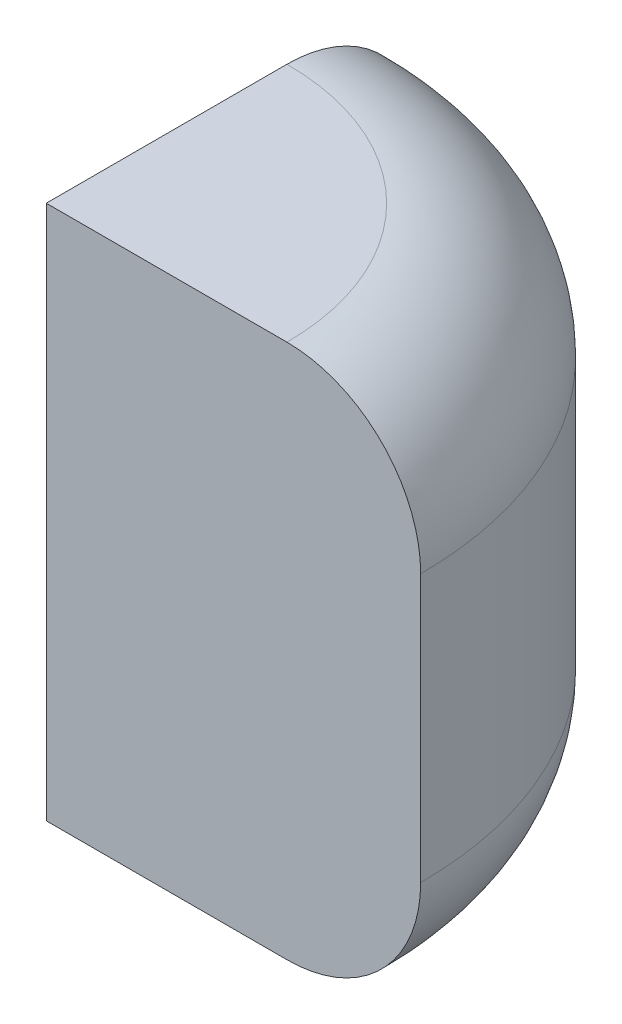
SolidWorks part; units mm, degrees
ref_plane "Front Plane" through (0, 0, 0) normal (0, 0, 1) x (1, 0, 0)
ref_plane "Top Plane" through (0, 0, 0) normal (0, 1, 0) x (1, 0, 0)
ref_plane "Right Plane" through (0, 0, 0) normal (1, 0, 0) x (0, 0, -1)
sketch "Sketch1" plane through (0, 0, 0) normal (0, 0, 1) x (1, 0, 0)
  line L1 (0, 0) -> (57.15, 0)
  line L2 (0, 0) -> (0, 127)
  line L3 (0, 127) -> (57.15, 127)
  line L4 (88.9, 31.75) -> (88.9, 95.25)
  arc A0 (57.15, 0) -> (88.9, 31.75) centre (57.15, 31.75) ccw
  arc A1 (57.15, 127) -> (88.9, 95.25) centre (57.15, 95.25) cw
  point P7 (0, 0)
  point P10 (0, 127)
  point P11 (88.9, 127)
  dimension "D3" = 31.75
  dimension "D1" = 127
  dimension "D2" = 88.9
revolve "Revolve1" add sketch "Sketch1" angle 90 about L2
